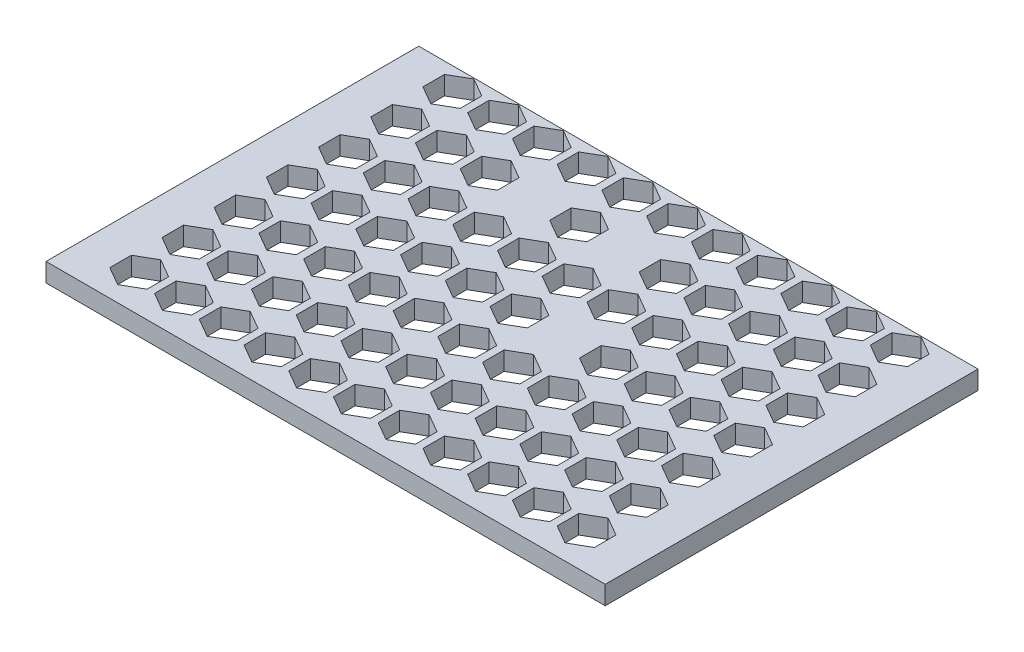
SolidWorks part; units mm, degrees
ref_plane "Front Plane" through (0, 0, 0) normal (0, 0, 1) x (1, 0, 0)
ref_plane "Top Plane" through (0, 0, 0) normal (0, 1, 0) x (1, 0, 0)
ref_plane "Right Plane" through (0, 0, 0) normal (1, 0, 0) x (0, 0, -1)
sketch "Sketch1" plane through (0, 0, 0) normal (0, 1, 0) x (1, 0, 0)
  line L1 (0, 0) -> (381, 0)
  line L2 (0, 0) -> (0, 254)
  line L3 (0, 254) -> (381, 254)
  line L4 (381, 0) -> (381, 254)
  dimension "D1" = 254
  dimension "D2" = 381
extrude "Boss-Extrude1" add sketch "Sketch1" along normal blind 12.7
sketch "Sketch2" plane through (0, 12.7, 0) normal (0, 1, 0) x (1, 0, 0)
  line L0 (38.1, 10.7353) -> (50.8, 18.0677)
  line L1 (38.1, 40.0647) -> (25.4, 32.7323)
  line L2 (25.4, 32.7323) -> (25.4, 18.0677)
  line L3 (25.4, 18.0677) -> (38.1, 10.7353)
  line L4 (50.8, 18.0677) -> (50.8, 32.7323)
  line L5 (50.8, 32.7323) -> (38.1, 40.0647)
  line L6 (0, 254) -> (0, 0) construction
  line L7 (0, 0) -> (381, 0) construction
  circle A0 centre (38.1, 25.4) radius 12.7 construction
  dimension "D1" = 25.4
  dimension "D2" = 25.4
  dimension "D3" = 25.4
extrude "Cut-Extrude1" cut sketch "Sketch2" against normal through all
pattern_linear "LPattern1" count 11 spacing 30.48 along (1, 0, 0) count 7 spacing 35.56 along (0, 0, -1) skipping (3, 5), (5, 5), (6, 3) of "Cut-Extrude1"
